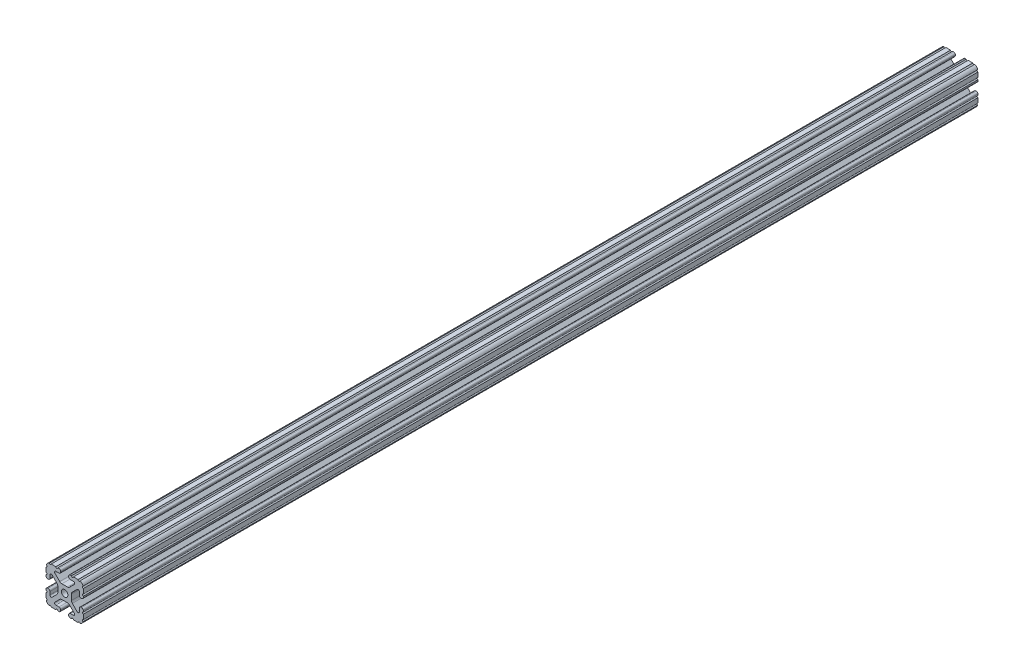
SolidWorks part; units mm, degrees
ref_plane "Front Plane" through (0, 0, 0) normal (0, 0, 1) x (1, 0, 0)
ref_plane "Top Plane" through (0, 0, 0) normal (0, 1, 0) x (1, 0, 0)
ref_plane "Right Plane" through (0, 0, 0) normal (1, 0, 0) x (0, 0, -1)
sketch "Sketch2" plane through (0, 0, 0) normal (0, 0, 1) x (1, 0, 0)
  line L0 (0, 19.05) -> (0, -19.05) construction
  line L1 (-19.05, 0) -> (19.05, 0) construction
  line L2 (4.064, -19.05) -> (19.05, -19.05)
  line L3 (19.05, -19.05) -> (19.05, -4.064)
  line L4 (4.064, -19.05) -> (4.064, -14.986)
  line L5 (4.064, -14.986) -> (12.1123, -14.986)
  line L6 (12.1123, -14.986) -> (4.1113, -6.985)
  line L7 (0, 0) -> (19.05, -19.05) construction
  line L8 (19.05, -4.064) -> (14.986, -4.064)
  line L9 (14.986, -4.064) -> (14.986, -12.1123)
  line L10 (14.986, -12.1123) -> (6.985, -4.1113)
  circle A0 centre (0, 0) radius 3.3274
  arc A1 (8.9963, -14.986) -> (9.909, -12.7826) centre (8.9963, -13.6953) ccw construction
  point P8 (0, -6.985)
  dimension "Center Hole Diameter" = 6.6548
  dimension "Rail Height" = 38.1
  dimension "Rail Width" = 38.1
  dimension "T-Slot Width" = 8.128
  dimension "Slot Inner Width" = 20.574
  dimension "Thickness" = 4.064
  dimension "Slot Depth" = 8.001
  dimension "D1" = 4.064
sketch "Sketch3" plane through (0, 0, 0) normal (1, 0, 0) x (0, 0, -1)
  line L0 (-457.2, -19.05) -> (457.2, -19.05) construction
  line L1 (-431.8, 0) -> (431.8, 0) construction
  dimension "Length" = 914.4
  dimension "D1" = 25.4
sketch "Sketch4" plane through (0, 0, 0) normal (0, 0, 1) x (1, 0, 0)
  line L0 (5.7912, -19.05) -> (14.3002, -19.05)
  line L1 (4.064, -19.05) -> (19.05, -19.05) construction
  line L2 (4.064, -19.05) -> (4.064, -14.986) construction
  line L3 (4.064, -14.986) -> (12.1123, -14.986) construction
  line L4 (4.064, -16.7132) -> (4.064, -17.3228)
  line L5 (5.7912, -14.986) -> (8.9963, -14.986)
  line L6 (0, -6.985) -> (2.833, -6.985)
  line L7 (12.1123, -14.986) -> (4.1113, -6.985) construction
  line L8 (5.0152, -7.8889) -> (9.909, -12.7826)
  line L9 (19.05, -19.05) -> (19.05, -4.064) construction
  line L10 (14.986, -12.1123) -> (6.985, -4.1113) construction
  line L11 (14.986, -4.064) -> (14.986, -12.1123) construction
  line L12 (14.986, -8.9963) -> (14.986, -5.7912)
  line L13 (19.05, -4.064) -> (14.986, -4.064) construction
  line L14 (16.7132, -4.064) -> (17.3228, -4.064)
  line L15 (19.05, -5.7912) -> (19.05, -14.3002)
  line L16 (12.7826, -9.909) -> (7.8889, -5.0152)
  line L17 (6.985, 0) -> (6.985, -2.833)
  line L18 (-19.05, 0) -> (19.05, 0) construction
  line L19 (0, -6.985) -> (0, -3.3274)
  line L20 (0, 19.05) -> (0, -19.05) construction
  line L21 (6.985, 0) -> (3.3274, 0)
  arc A0 (4.064, -17.3228) -> (5.7912, -19.05) centre (5.7912, -17.3228) ccw
  arc A2 (4.064, -16.7132) -> (5.7912, -14.986) centre (5.7912, -16.7132) cw
  arc A3 (8.9963, -14.986) -> (9.909, -12.7826) centre (8.9963, -13.6953) ccw
  arc A4 (2.833, -6.985) -> (5.0152, -7.8889) centre (2.833, -10.0711) cw
  arc A5 (14.3002, -19.05) -> (19.05, -14.3002) centre (14.3002, -14.3002) ccw
  arc A6 (12.7826, -9.909) -> (14.986, -8.9963) centre (13.6953, -8.9963) ccw
  arc A7 (14.986, -5.7912) -> (16.7132, -4.064) centre (16.7132, -5.7912) cw
  arc A8 (17.3228, -4.064) -> (19.05, -5.7912) centre (17.3228, -5.7912) cw
  arc A9 (7.8889, -5.0152) -> (6.985, -2.833) centre (10.0711, -2.833) cw
  circle A10 centre (0, 0) radius 3.3274 construction
  arc A11 (0, -3.3274) -> (3.3274, 0) centre (0, 0) ccw
  dimension "D1" = 4.7498
  dimension "D2" = 3.0861
  dimension "D3" = 1.7272
extrude "Boss-Extrude1" add sketch "Sketch4" along normal mid plane 914.4
sketch "Sketch5" plane through (0, 0, 0) normal (0, 0, 1) x (1, 0, 0)
  line L0 (4.064, -19.05) -> (19.05, -19.05) construction
  line L1 (5.7912, -14.986) -> (8.9963, -14.986) construction
  line L3 (0, 0) -> (19.05, -19.05) construction
  line L4 (8.9963, -14.986) -> (8.9963, -19.05) construction
  line L5 (12.1123, -14.986) -> (4.1113, -6.985) construction
  circle A0 centre (14.7395, -19.05) radius 1.016
  circle A1 centre (7.9803, -19.05) radius 1.016
  circle A2 centre (19.05, -14.7395) radius 1.016
  circle A3 centre (19.05, -7.9803) radius 1.016
  point P10 (7.3938, -14.986)
  point P12 (13.6953, -8.9963)
extrude "Cut-Extrude1" cut sketch "Sketch5" against normal through all both and the other way through all
mirror "Mirror1" about plane through (0, 0, 0) normal (1, 0, 0) of bodies 137 134
mirror "Mirror2" about plane through (0, 0, 0) normal (0, 1, 0) of bodies 135
equation "\"D1@Boss-Extrude1\"=\"Length@Sketch3\""
equation "\"D1@Sketch2\"=\"Thickness@Sketch2\""
equation "\"D2@Sketch4\"=\"Slot Inner Width@Sketch2\"*0.15"
equation "\"D1@Sketch4\"=\"D3@Sketch4\"*2.75"
equation "\"D3@Sketch4\"=\"Thickness@Sketch2\"*0.425"
equation "\"D1@Sketch5\"=\"Thickness@Sketch2\"*0.5"
